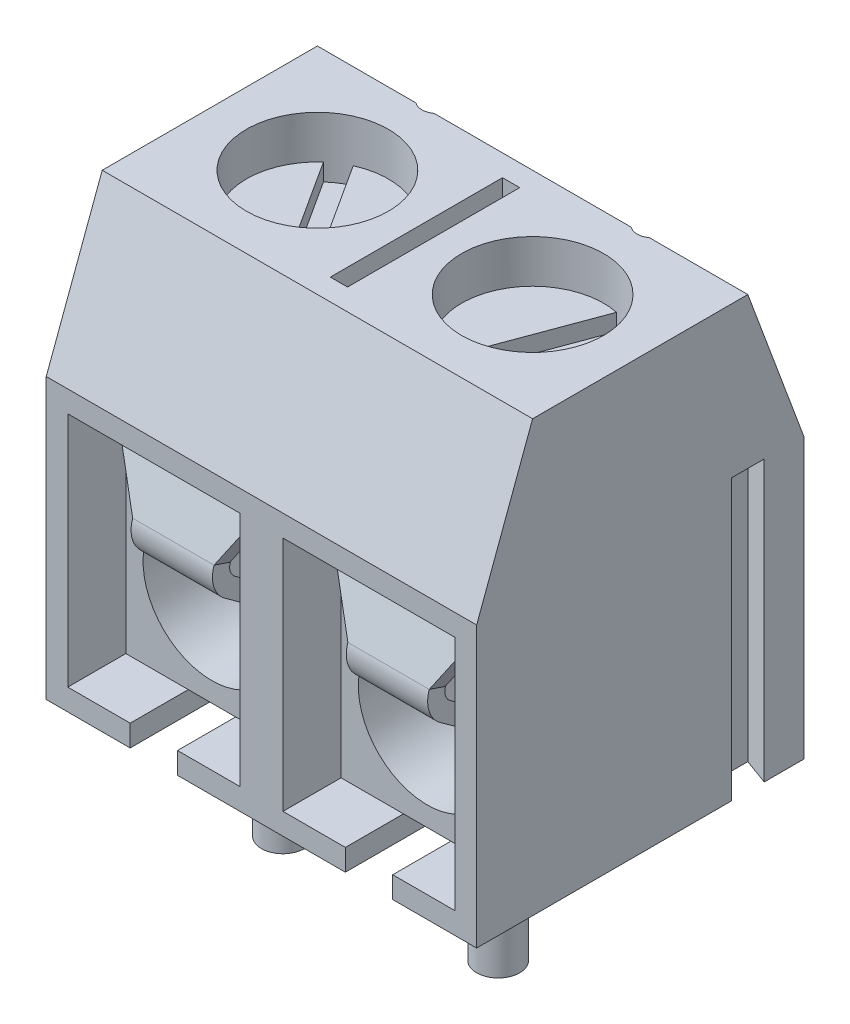
SolidWorks part; units mm, degrees
ref_plane "Front Plane" through (0, 0, 0) normal (0, 0, 1) x (1, 0, 0)
ref_plane "Top Plane" through (0, 0, 0) normal (0, 1, 0) x (1, 0, 0)
ref_plane "Right Plane" through (0, 0, 0) normal (1, 0, 0) x (0, 0, -1)
sketch "Sketch1" plane through (0, 0, 0) normal (0, 1, 0) x (1, 0, 0)
  line L1 (-5, 3.8) -> (5, 3.8)
  line L2 (-5, 3.8) -> (-5, -3.8)
  line L3 (-5, -3.8) -> (5, -3.8)
  line L4 (5, 3.8) -> (5, -3.8)
  dimension "D1" = 10
  dimension "D2" = 5
  dimension "D3" = 7.6
  dimension "D4" = 3.8
extrude "Extrude1" add sketch "Sketch1" along normal blind 10
sketch "Sketch2" plane through (0, 0, 0) normal (1, 0, 0) x (0, 0, -1)
  line L0 (2.5, 10) -> (3.8, 6.5)
  line L1 (3.8, 10) -> (-3.8, 10) construction
  line L2 (3.8, 10) -> (3.8, 0) construction
  line L3 (3.8, 6.5) -> (-3.8, 6.5) construction
  line L4 (-3.8, 10) -> (-3.8, 0) construction
  line L5 (-3.8, 6.5) -> (-2.5, 10)
  line L6 (-2.5, 10) -> (2.5, 10)
  line L7 (3.8, 6.5) -> (3.8, 0)
  line L8 (3.8, 0) -> (-3.8, 0)
  line L9 (-3.8, 0) -> (-3.8, 6.5)
  dimension "D1" = 5
  dimension "D2" = 2.5
  dimension "D3" = 3.5
extrude "Cut-Extrude1" cut sketch "Sketch2" against normal through all and the other way through all flip side to cut
sketch "Sketch3" plane through (0, 10, 0) normal (0, 1, 0) x (-1, 0, 0)
  line L0 (5, -2.5) -> (-5, -2.5) construction
  line L1 (0.2, -2) -> (-0.2, -2)
  line L2 (0.2, -2) -> (0.2, 2)
  line L3 (0.2, 2) -> (-0.2, 2)
  line L4 (-0.2, -2) -> (-0.2, 2)
  circle A0 centre (2.5, 0) radius 1.65
  circle A1 centre (-2.5, 0) radius 1.65
  circle A2 centre (2.5, -2.78) radius 0.35
  circle A3 centre (-2.5, -2.78) radius 0.35
  dimension "D7" = 3.3
  dimension "D8" = 0.7
  dimension "D1" = 0.4
  dimension "D2" = 0.2
  dimension "D3" = 4
  dimension "D4" = 2
  dimension "D5" = 2.5
  dimension "D6" = 2.5
  dimension "D9" = 0.28
extrude "Cut-Extrude2" cut sketch "Sketch3" against normal blind 4
sketch "Sketch4" plane through (0, 0, 3.8) normal (0, 0, 1) x (1, 0, 0)
  line L0 (-5, 6.5) -> (-5, 0) construction
  line L1 (-4.5, 6) -> (-0.5, 6)
  line L2 (-4.5, 6) -> (-4.5, 0.5)
  line L3 (-4.5, 0.5) -> (-0.5, 0.5)
  line L4 (-0.5, 6) -> (-0.5, 0.5)
  line L5 (0.5, 6) -> (4.5, 6)
  line L6 (0.5, 6) -> (0.5, 0.5)
  line L7 (0.5, 0.5) -> (4.5, 0.5)
  line L8 (4.5, 6) -> (4.5, 0.5)
  line L9 (-5, 6.5) -> (5, 6.5) construction
  line L10 (-5, 0) -> (5, 0) construction
  line L11 (5, 6.5) -> (5, 0) construction
  dimension "D1" = 0.5
  dimension "D2" = 0.5
  dimension "D3" = 0.5
  dimension "D4" = 1
  dimension "D5" = 0.5
extrude "Cut-Extrude3" cut sketch "Sketch4" against normal offset from surface (5.6 mm away) 2 up to face at (0, 3.25, -3.8)
sketch "Sketch5" plane through (0, 0, -1.8) normal (0, 0, 1) x (1, 0, 0)
  line L0 (-4.5, 5.6) -> (-0.5, 5.6)
  line L1 (0.5, 5.6) -> (4.5, 5.6)
  line L2 (-4.5, 5.6) -> (-4.5, 0.5)
  line L3 (-0.5, 5.6) -> (-0.5, 6) construction
  line L4 (-4.5, 6) -> (-4.5, 0.5)
  line L5 (-4.5, 0.5) -> (-0.5, 0.5)
  line L6 (-0.5, 0.5) -> (-0.5, 6)
  line L7 (-0.5, 6) -> (-4.5, 6)
  line L8 (-4.5, 6) -> (-4.5, 5.6) construction
  line L9 (-4.5, 0.5) -> (-0.5, 0.5)
  line L10 (-0.5, 0.5) -> (-0.5, 5.6)
  line L11 (-0.5, 6) -> (-4.5, 6) construction
  line L12 (0.5, 6) -> (0.5, 0.5)
  line L13 (0.5, 0.5) -> (4.5, 0.5)
  line L14 (4.5, 0.5) -> (4.5, 6)
  line L15 (4.5, 6) -> (0.5, 6)
  line L16 (0.5, 6) -> (0.5, 5.6) construction
  line L17 (0.5, 0.5) -> (4.5, 0.5)
  line L18 (4.5, 0.5) -> (4.5, 5.6)
  line L19 (4.5, 6) -> (0.5, 6) construction
  line L20 (0.5, 5.6) -> (0.5, 0.5)
  line L21 (4.5, 5.6) -> (4.5, 6) construction
  dimension "D3" = 0.4
  dimension "D1" = 0
  dimension "D2" = 0
extrude "Extrude2" add sketch "Sketch5" along normal offset from surface (4.25 mm away) 1.35 up to face at (2.5, 3.25, 3.8)
sketch "Sketch6" plane through (0, 0, 2.45) normal (0, 0, 1) x (1, 0, 0)
  circle A0 centre (-2.5, 2.5543) radius 1.6
  circle A1 centre (2.5, 2.5543) radius 1.6
  dimension "D1" = 3.2
extrude "Cut-Extrude4" cut sketch "Sketch6" against normal up to surface (4.25 mm away) up to face at (-2.5, 5.8, -1.8)
ref_plane "Plane1" through (-2.5, 0, 0) normal (1, 0, 0) x (0, 0, -1)
ref_plane "Plane2" through (2.5, 0, 0) normal (1, 0, 0) x (0, 0, -1)
sketch "Sketch7" plane through (0, 0, 0) normal (0, 1, 0) x (1, 0, 0)
  line L0 (-5, 2.5) -> (-5, -2.5) construction
  line L1 (-5.6, 3.1) -> (-5, 2.8816)
  line L2 (-5.6, 3.1) -> (-5.6, 1.9)
  line L3 (-5.6, 1.9) -> (-5, 2.1184)
  line L4 (-5, 2.8816) -> (-5, 2.1184)
  line L5 (5, 3.8) -> (-5, 3.8) construction
  dimension "D1" = 1.2
  dimension "D2" = 70
  dimension "D3" = 70
  dimension "D4" = 0.6
  dimension "D5" = 1.9
extrude "Extrude3" add sketch "Sketch7" along normal up to vertex (6.5 mm away) up to point (-5, 6.5, -3.8)
sketch "Sketch9" plane through (0, 0, 0) normal (0, 1, 0) x (1, 0, 0)
  line L0 (5, -3.8) -> (5, 3.8) construction
  line L8 (5, 2.8816) -> (4.4, 3.1)
  line L9 (5, 2.1184) -> (5, 2.8816)
  line L10 (4.4, 1.9) -> (5, 2.1184)
  line L11 (4.4, 3.1) -> (4.4, 1.9)
extrude "Cut-Extrude5" cut sketch "Sketch9" along normal up to vertex (6.5 mm away) up to point (5, 6.5, -3.8)
sketch "Sketch10" plane through (0, 0, 3.8) normal (0, 0, 1) x (1, 0, 0)
  line L0 (-4.5, 0.5) -> (-0.5, 0.5) construction
  line L1 (-3.05, 0.5) -> (-1.95, 0.5)
  line L2 (-3.05, 0.5) -> (-3.05, 0)
  line L3 (-3.05, 0) -> (-1.95, 0)
  line L4 (-1.95, 0.5) -> (-1.95, 0)
  line L5 (-5, 0) -> (5, 0) construction
  line L6 (0.5, 0.5) -> (4.5, 0.5) construction
  line L7 (1.95, 0.5) -> (3.05, 0.5)
  line L8 (1.95, 0.5) -> (1.95, 0)
  line L9 (1.95, 0) -> (3.05, 0)
  line L10 (3.05, 0.5) -> (3.05, 0)
  dimension "D1" = 1.1
  dimension "D2" = 0.55
  dimension "D3" = 0.55
extrude "Cut-Extrude6" cut sketch "Sketch10" against normal blind 3.6
sketch "Sketch11" plane through (0, 0.5, 0) normal (0, -1, 0) x (1, 0, 0)
  line L0 (-2.5, -1.8) -> (-2.5, 2.45) construction
  line L1 (2.5, -1.8) -> (2.5, 2.45) construction
  line L2 (-3.05, 0.2) -> (-1.95, 0.2) construction
  circle A0 centre (-2.5, 0.8) radius 0.5
  circle A1 centre (2.5, 0.8) radius 0.5
  dimension "D1" = 0.6
extrude "Extrude4" add sketch "Sketch11" along normal blind 3.5
sketch "Sketch12" plane through (0, 6, 0) normal (0, -1, 0) x (1, 0, 0)
  circle A0 centre (2.5, 0) radius 1.65 construction
  circle A1 centre (-2.5, 0) radius 1.65 construction
  circle A2 centre (2.5, 0) radius 1.65
  circle A3 centre (-2.5, 0) radius 1.65
extrude "Extrude5" add sketch "Sketch12" against normal offset from surface (3 mm away) 1 up to face at (0, 10, -1.2325)
sketch "Sketch13" plane through (0, 9, 0) normal (0, 1, 0) x (-1, 0, 0)
  line L1 (3.5943, -1.2349) -> (1.8258, 1.506)
  line L2 (3.1742, -1.506) -> (1.4057, 1.2349)
  line L5 (-2.8322, -1.6162) -> (-1.699, 1.4425)
  line L6 (-3.301, -1.4425) -> (-2.1678, 1.6162)
  circle A0 centre (-2.5, 0) radius 1.65 construction
  circle A1 centre (2.5, 0) radius 1.65 construction
  arc A2 (-1.699, 1.4425) -> (-2.1678, 1.6162) centre (-2.5, 0) ccw
  arc A3 (1.8258, 1.506) -> (1.4057, 1.2349) centre (2.5, 0) ccw
  arc A4 (-3.301, -1.4425) -> (-2.8322, -1.6162) centre (-2.5, 0) ccw
  arc A5 (3.1742, -1.506) -> (3.5943, -1.2349) centre (2.5, 0) ccw
  dimension "D1" = 0.5
  dimension "D2" = 0.5
extrude "Cut-Extrude7" cut sketch "Sketch13" against normal blind 0.4
sketch "Sketch14" plane through (-2.5, 0, 0) normal (-1, 0, 0) x (0, 0, 1)
  line L0 (2.45, 5.6) -> (3.0389, 3.8617)
  line L1 (3.0389, 3.8617) -> (0.1672, 1.7876)
  line L2 (0.1672, 1.7876) -> (-0.5464, 2.0974)
  line L3 (-0.5464, 2.0974) -> (-0.7057, 1.7305)
  line L4 (-0.7057, 1.7305) -> (0.2168, 1.33)
  line L5 (0.2168, 1.33) -> (3.5125, 3.7103)
  line L6 (-1.8, 5.6) -> (2.45, 5.6)
  line L7 (2.45, 5.6) -> (2.45, 0.5)
  line L8 (2.45, 0.5) -> (3.8, 0.5)
  line L9 (3.8, 0.5) -> (3.8, 6)
  line L10 (3.8, 6) -> (-1.8, 6)
  line L11 (-1.8, 6) -> (-1.8, 5.6)
  line L12 (-1.8, 5.6) -> (2.45, 5.6)
  line L13 (3.5125, 3.7103) -> (2.7368, 6)
  line L14 (2.7368, 6) -> (-1.8, 6)
  line L17 (-1.8, 6) -> (-1.8, 5.6)
  dimension "D2" = 0.4
  dimension "D3" = 0.4
  dimension "D4" = 0.4
  dimension "D1" = 0
extrude "Extrude6" add sketch "Sketch14" along normal blind 0.945 and the other way blind 0.945
sketch "Sketch15" plane through (0, 1.4494, 4.2784) normal (0, 0.3209, 0.9471) x (1, 0, 0)
  line L2 (-1.555, 4.8) -> (-1.555, 2.904)
  line L3 (-3.445, 4.8) -> (-3.445, 2.904)
  line L4 (-1.555, 2.904) -> (-0.51, 4.8)
  line L5 (-0.51, 4.8) -> (-1.555, 4.8)
  line L6 (-3.445, 2.904) -> (-4.49, 4.8)
  line L8 (-4.49, 4.8) -> (-3.445, 4.8)
extrude "Extrude9" add sketch "Sketch15" against normal blind 0.39
pattern_linear "LPattern1" count 2 spacing 5 along (1, 0, 0) of "Extrude6", "Extrude9"
fillet "Fillet1" radius 0.3 4 edges at (-2.5, 3.8617, 3.0389) (-2.5, 1.7876, 0.1672) (2.5, 1.7876, 0.1672) (2.5, 3.8617, 3.0389)
fillet "Fillet2" radius 0.7 4 edges at (-2.5, 3.7103, 3.5125) (-2.5, 1.33, 0.2168) (2.5, 1.33, 0.2168) (2.5, 3.7103, 3.5125)
